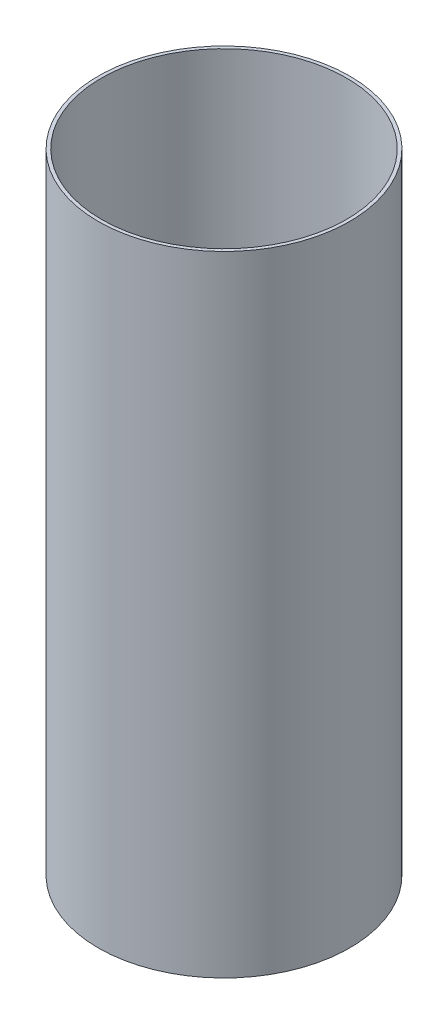
SolidWorks part; units mm, degrees
material "A-Glass Fiber"
ref_plane "Front Plane" through (0, 0, 0) normal (0, 0, 1) x (1, 0, 0)
ref_plane "Top Plane" through (0, 0, 0) normal (0, 1, 0) x (1, 0, 0)
ref_plane "Right Plane" through (0, 0, 0) normal (1, 0, 0) x (0, 0, -1)
sketch "Sketch1" plane through (0, 0, 0) normal (0, 1, 0) x (1, 0, 0)
  circle A0 centre (0, 0) radius 74.2
  circle A1 centre (0, 0) radius 76.2
  dimension "D1" = 148.4
  dimension "D2" = 152.4
extrude "Boss-Extrude1" add sketch "Sketch1" along normal blind 381
